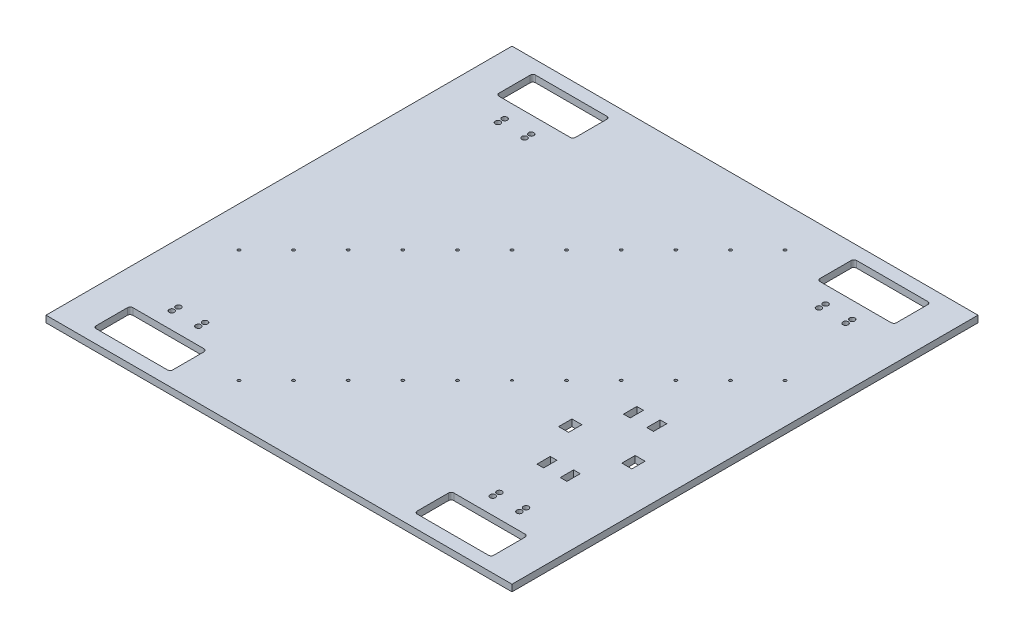
SolidWorks part; units mm, degrees
ref_plane "Front Plane" through (0, 0, 0) normal (0, 0, 1) x (1, 0, 0)
ref_plane "Top Plane" through (0, 0, 0) normal (0, 1, 0) x (1, 0, 0)
ref_plane "Right Plane" through (0, 0, 0) normal (1, 0, 0) x (0, 0, -1)
sketch "Sketch1" plane through (0, 0, 0) normal (0, 1, 0) x (1, 0, 0)
  line L1 (0, 0) -> (700, 0)
  line L2 (0, 0) -> (0, 700)
  line L3 (0, 700) -> (700, 700)
  line L4 (700, 0) -> (700, 700)
  dimension "D1" = 700
  dimension "D2" = 700
extrude "Boss-Extrude1" add sketch "Sketch1" along normal blind 10
sketch "Sketch2" plane through (0, 10, 0) normal (0, 1, 0) x (1, 0, 0)
  line L0 (0, 700) -> (0, 0) construction
  line L1 (51.4, 20) -> (166.4, 20)
  line L2 (51.4, 20) -> (51.4, 75)
  line L3 (51.4, 75) -> (166.4, 75)
  line L4 (166.4, 20) -> (166.4, 75)
  line L5 (51.4, 20) -> (166.4, 75) construction
  line L6 (51.4, 75) -> (166.4, 20) construction
  line L7 (88.9, 110) -> (128.9, 110) construction
  line L8 (88.9, 110) -> (88.9, 100) construction
  line L9 (88.9, 100) -> (128.9, 100) construction
  line L10 (128.9, 110) -> (128.9, 100) construction
  line L11 (88.9, 110) -> (128.9, 100) construction
  line L12 (88.9, 100) -> (128.9, 110) construction
  line L13 (0, 0) -> (700, 0) construction
  circle A0 centre (88.9, 110) radius 4
  circle A1 centre (128.9, 110) radius 4
  circle A2 centre (128.9, 100) radius 4
  circle A3 centre (88.9, 100) radius 4
  point P4 (108.9, 47.5)
  point P10 (108.9, 105)
  point P18 (108.9, 75)
  point P19 (108.9, 100)
  dimension "D3" = 8
  dimension "D1" = 10
  dimension "D2" = 40
  dimension "D4" = 88.9
  dimension "D5" = 25
  dimension "D6" = 100
  dimension "D7" = 55
  dimension "D8" = 115
extrude "Cut-Extrude2" cut sketch "Sketch2" against normal blind 10 contours L2 L1 L4 L3 | A2 | A1 | A0 | A3
fillet "Fillet1" radius 4 4 edges at (166.4, 5, -20) (166.4, 5, -75) (51.4, 5, -20) (51.4, 5, -75)
ref_plane "Plane1" through (0, 0, -350) normal (0, 0, 1) x (1, 0, 0)
ref_plane "Plane2" through (350, 0, 0) normal (-1, 0, 0) x (0, 0, 1)
mirror "Mirror3" about plane through (0, 0, -350) normal (0, 0, 1) of "Cut-Extrude2" second plane through (350, 0, 0) second plane normal (-1, 0, 0)
fillet "Fillet2" radius 4 12 edges at (166.4, 5, -625) (51.4, 5, -625) (51.4, 5, -680) (166.4, 5, -680) (648.6, 5, -625) (533.6, 5, -625) (533.6, 5, -680) (648.6, 5, -680) (533.6, 5, -75) (648.6, 5, -75) (648.6, 5, -20) (533.6, 5, -20)
sketch "Sketch3" plane through (0, 10, 0) normal (0, 1, 0) x (1, 0, 0)
  line L0 (0, 0) -> (700, 700) construction
  line L1 (0, 700) -> (700, 0) construction
  line L2 (-79.5535, 90.1521) -> (628.441, 798.1466) construction
  circle A1 centre (470.2082, 639.9138) radius 2.1
  circle A2 centre (60.0862, 229.7918) radius 2.1
  circle A3 centre (639.9138, 470.2082) radius 2.1
  circle A6 centre (429.196, 598.9016) radius 2.1
  circle A7 centre (388.1838, 557.8894) radius 2.1
  circle A8 centre (347.1716, 516.8772) radius 2.1
  circle A9 centre (306.1594, 475.865) radius 2.1
  circle A10 centre (265.1472, 434.8528) radius 2.1
  circle A11 centre (224.135, 393.8406) radius 2.1
  circle A12 centre (183.1228, 352.8284) radius 2.1
  circle A13 centre (142.1106, 311.8162) radius 2.1
  circle A14 centre (101.0984, 270.804) radius 2.1
  circle A15 centre (229.7918, 60.0862) radius 2.1
  circle A16 centre (270.804, 101.0984) radius 2.1
  circle A17 centre (311.8162, 142.1106) radius 2.1
  circle A18 centre (352.8284, 183.1228) radius 2.1
  circle A19 centre (393.8406, 224.135) radius 2.1
  circle A20 centre (434.8528, 265.1472) radius 1.6
  circle A21 centre (475.865, 306.1594) radius 2.1
  circle A22 centre (516.8772, 347.1716) radius 2.1
  circle A23 centre (557.8894, 388.1838) radius 2.1
  circle A24 centre (598.9016, 429.196) radius 2.1
  point P56 (598.9016, 429.196)
  dimension "D3" = 4.2
  dimension "D1" = 120
  dimension "D5" = 10
extrude "Cut-Extrude3" cut sketch "Sketch3" against normal through all
sketch "Sketch4" plane through (0, 10, 0) normal (0, 1, 0) x (1, 0, 0)
  line L0 (0, 0) -> (700, 0) construction
  line L5 (597.5, 325) -> (607.5, 325)
  line L6 (597.5, 325) -> (597.5, 305)
  line L7 (597.5, 305) -> (607.5, 305)
  line L8 (607.5, 325) -> (607.5, 305)
  line L9 (597.5, 195) -> (607.5, 195)
  line L10 (597.5, 195) -> (597.5, 175)
  line L11 (597.5, 175) -> (607.5, 175)
  line L12 (607.5, 195) -> (607.5, 175)
  line L21 (562.5, 325) -> (572.5, 325)
  line L22 (562.5, 325) -> (562.5, 305)
  line L23 (562.5, 305) -> (572.5, 305)
  line L24 (572.5, 325) -> (572.5, 305)
  line L25 (562.5, 195) -> (572.5, 195)
  line L26 (562.5, 195) -> (562.5, 175)
  line L27 (562.5, 175) -> (572.5, 175)
  line L28 (572.5, 195) -> (572.5, 175)
  line L33 (700, 0) -> (700, 700) construction
  line L34 (530, 260) -> (545, 260)
  line L35 (530, 260) -> (530, 240)
  line L36 (530, 240) -> (545, 240)
  line L37 (545, 260) -> (545, 240)
  line L38 (625, 260) -> (640, 260)
  line L39 (625, 260) -> (625, 240)
  line L40 (625, 240) -> (640, 240)
  line L41 (640, 260) -> (640, 240)
  point P43 (632.5, 240)
  dimension "D6" = 10
  dimension "D7" = 10
  dimension "D8" = 10
  dimension "D9" = 10
  dimension "D12" = 20
  dimension "D13" = 20
  dimension "20" = 20
  dimension "D14" = 20
  dimension "D17" = 80
  dimension "D18" = 60
  dimension "D19" = 15
  dimension "D20" = 20
  dimension "D21" = 20
  dimension "D23" = 110
  dimension "D24" = 45
  dimension "D25" = 240
  dimension "D28" = 15
extrude "Cut-Extrude4" cut sketch "Sketch4" against normal through all
